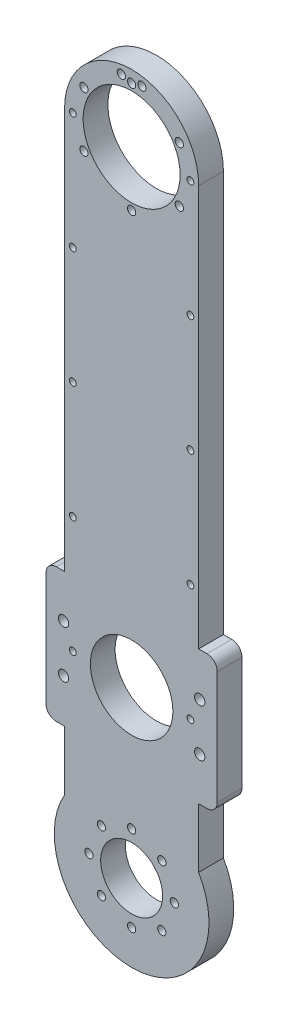
SolidWorks part; units mm, degrees
material "Alumina"
ref_plane "Front Plane" through (0, 0, 0) normal (0, 0, 1) x (1, 0, 0)
ref_plane "Top Plane" through (0, 0, 0) normal (0, 1, 0) x (1, 0, 0)
ref_plane "Right Plane" through (0, 0, 0) normal (1, 0, 0) x (0, 0, -1)
sketch "Sketch1" plane through (0, 0, 0) normal (0, 0, 1) x (1, 0, 0)
  line L0 (0, 199.0835) -> (0, 0) construction
  line L3 (-32.5, 199.0835) -> (-32.5, -89.2082)
  line L4 (32.5, 199.0835) -> (32.5, -89.2082)
  circle A0 centre (0, 199.0835) radius 23.5
  circle A1 centre (0, 199.0835) radius 32.5
  circle A2 centre (0, -107.9165) radius 15
  circle A3 centre (0, -107.9165) radius 37.5
  circle A6 centre (0, -27.9165) radius 20
  dimension "D1" = 47
  dimension "D2" = 65
  dimension "D3" = 30
  dimension "D4" = 75
  dimension "D5" = 40
  dimension "D6" = 80
  dimension "D8" = 307
extrude "Boss-Extrude1" add sketch "Sketch1" along normal blind 12
sketch "Sketch2" plane through (0, 0, 0) normal (0, 0, -1) x (-1, 0, 0)
  line L0 (0, -107.9165) -> (-15, -107.9165) construction
  circle A0 centre (-20.7, -107.9165) radius 2
  circle A1 centre (0, -107.9165) radius 15 construction
  dimension "D1" = 4
  dimension "D2" = 5.7
extrude "Cut-Extrude1" cut sketch "Sketch2" against normal blind 13
pattern_circular "CirPattern1" count 8 over 360 about axis through (0, -107.9165, 0) along (0, 0, 1) of "Cut-Extrude1"
sketch "Sketch3" plane through (0, 0, 0) normal (0, 0, -1) x (-1, 0, 0)
  line L1 (-32.5, 199.0835) -> (-32.5, -89.2082) construction
  circle A0 centre (0, 225.7835) radius 2
  circle A1 centre (0, 199.0835) radius 23.5 construction
  dimension "D1" = 4
  dimension "D2" = 32.5
  dimension "D3" = 26.7
extrude "Cut-Extrude2" cut sketch "Sketch3" against normal blind 13
pattern_circular "CirPattern2" count 6 over 360 about axis through (0, 199.0835, 0) along (0, 0, 1) of "Cut-Extrude2"
sketch "Sketch6" plane through (0, 0, 0) normal (0, 0, -1) x (-1, 0, 0)
  circle A0 centre (0, 225.7835) radius 2 construction
  circle A2 centre (-5, 227.0835) radius 2
  circle A3 centre (5, 227.0835) radius 2
  arc A4 (32.5, 199.0835) -> (-32.5, 199.0835) centre (0, 199.0835) ccw construction
  dimension "D1" = 4
  dimension "D2" = 4
  dimension "D7" = 5
  dimension "D3" = 28
  dimension "D4" = 28
  dimension "D5" = 5
  dimension "D6" = 10
extrude "Cut-Extrude4" cut sketch "Sketch6" against normal through all
hole_wizard "Ø1.0mm Dowel Hole1" positions "Sketch8" profile "Sketch9" hole size "Ø1.0" standard "ANSI Metric" end condition through all
sketch "Sketch8" plane through (0, 0, 0) normal (0, 0, -1) x (-1, 0, 0)
  line L0 (0, 199.0835) -> (-0.9277, 199.0734)
  arc A0 (32.5, 199.0835) -> (-32.5, 199.0835) centre (0, 199.0835) ccw construction
  point P0 (-28.5, 199.0835)
  dimension "D1" = 28.5
sketch "Sketch9" plane through (28.5, 199.0835, 0) normal (1, 0, 0) x (0, 1, 0)
  line L0 (0, 0) -> (0, 12)
  line L1 (0, 12) -> (1.65, 12)
  line L2 (1.65, 12) -> (1.65, 0)
  line L5 (1.65, 0) -> (0, 0)
  line L11 (0, -6.35) -> (0, 107.95) construction
  dimension "Thru Hole Dia." = 3.3
  dimension "Thru Hole Depth" = 12
pattern_linear "LPattern1" count 5 spacing 56.5 along (0, -1, 0) of "Ø1.0mm Dowel Hole1"
mirror "Mirror1" about plane through (0, 0, 0) normal (1, 0, 0) of "LPattern1", "Ø1.0mm Dowel Hole1"
sketch "Sketch10" plane through (0, 0, 12) normal (0, 0, 1) x (1, 0, 0)
  line L0 (-32.5, 199.0835) -> (-32.5, -89.2082) construction
  line L1 (-32.5, 4.5835) -> (-41.5, 4.5835)
  line L2 (-32.5, 4.5835) -> (-32.5, -60.4165)
  line L3 (-32.5, -60.4165) -> (-41.5, -60.4165)
  line L4 (-41.5, 4.5835) -> (-41.5, -60.4165)
  arc A0 (-32.5, -89.2082) -> (32.5, -89.2082) centre (0, -107.9165) ccw construction
  circle A1 centre (-35.5, -5.7046) radius 2.5
  circle A2 centre (-35.5, -28.7046) radius 2.5
  dimension "D4" = 5
  dimension "D6" = 23
  dimension "D1" = 47.5
  dimension "D2" = 9
  dimension "D3" = 65
  dimension "D5" = 6
extrude "Boss-Extrude2" add sketch "Sketch10" against normal blind 12 contours L2 L1 L4 L3
fillet "Fillet1" radius 5 2 edges at (-41.5, -60.4165, 6) (-41.5, 4.5835, 6)
sketch "Sketch12" plane through (0, 0, 12) normal (0, 0, 1) x (1, 0, 0)
  line L0 (-41.5, -0.4165) -> (-41.5, -55.4165) construction
  line L1 (-32.5, 4.5835) -> (-36.5, 4.5835) construction
  circle A0 centre (-33, -16.4165) radius 2.5
  circle A1 centre (-33, -39.4165) radius 2.5
  dimension "D1" = 5
  dimension "D4" = 5
  dimension "D2" = 8.5
  dimension "D3" = 21
  dimension "D5" = 23
extrude "Cut-Extrude5" cut sketch "Sketch12" against normal blind 12
mirror "Mirror2" about plane through (0, 0, 0) normal (1, 0, 0) of "Boss-Extrude2", "Fillet1", "Cut-Extrude5"
